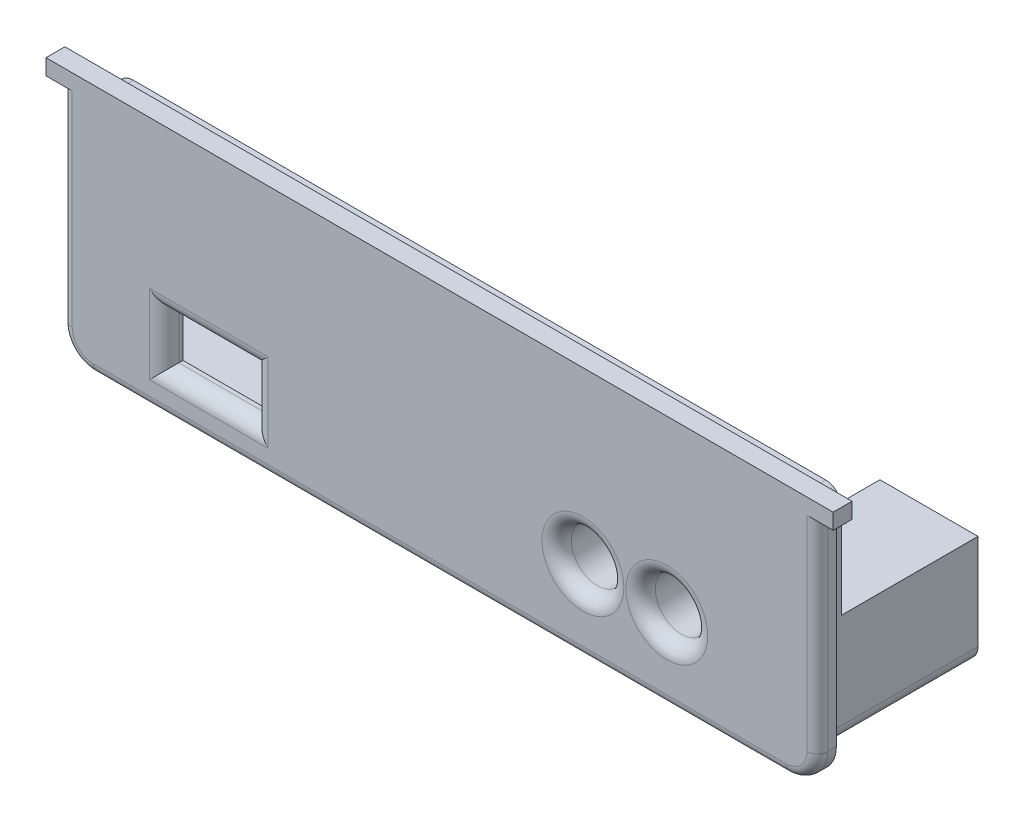
SolidWorks part; units mm, degrees
ref_plane "Front Plane" through (0, 0, 0) normal (0, 0, 1) x (1, 0, 0)
ref_plane "Top Plane" through (0, 0, 0) normal (0, 1, 0) x (1, 0, 0)
ref_plane "Right Plane" through (0, 0, 0) normal (1, 0, 0) x (0, 0, -1)
sketch "Sketch1" plane through (0, 0, 0) normal (0, 0, 1) x (1, 0, 0)
  line L1 (0, 0) -> (72, 0)
  line L2 (0, 0) -> (0, 22.5)
  line L3 (0, 24) -> (72, 24)
  line L4 (72, 0) -> (72, 22.5)
  line L5 (0, 24) -> (-1.5, 24)
  line L7 (0, 22.5) -> (-1.5, 22.5)
  line L8 (-1.5, 24) -> (-1.5, 22.5)
  line L9 (72, 24) -> (73.5, 24)
  line L11 (72, 22.5) -> (73.5, 22.5)
  line L12 (73.5, 24) -> (73.5, 22.5)
  dimension "D1" = 24
  dimension "D2" = 72
  dimension "D3" = 1.5
  dimension "D4" = 1.5
  dimension "D5" = 1.5
  dimension "D6" = 1.5
  dimension "D7" = 72
extrude "Boss-Extrude1" add sketch "Sketch1" along normal blind 1.8
sketch "Sketch2" plane through (0, 0, 0) normal (0, 0, -1) x (-1, 0, 0)
  line L0 (-73.5, 24) -> (1.5, 24) construction
  line L1 (-70.5, 22.5) -> (-1.5, 22.5)
  line L2 (-70.5, 22.5) -> (-70.5, 1.5)
  line L3 (-70.5, 1.5) -> (-1.5, 1.5)
  line L4 (-1.5, 22.5) -> (-1.5, 1.5)
  line L5 (-72, 0) -> (-72, 22.5) construction
  line L6 (0, 0) -> (-72, 0) construction
  line L7 (0, 22.5) -> (0, 0) construction
  line L9 (-68.5, 20.5) -> (-3.5, 20.5)
  line L10 (-68.5, 20.5) -> (-68.5, 3.5)
  line L11 (-68.5, 3.5) -> (-3.5, 3.5)
  line L12 (-3.5, 20.5) -> (-3.5, 3.5)
  dimension "D1" = 1.5
  dimension "D2" = 1.5
  dimension "D3" = 1.5
  dimension "D4" = 1.5
  dimension "D5" = 2
  dimension "D6" = 2
  dimension "D7" = 2
  dimension "D8" = 2
extrude "Boss-Extrude2" add sketch "Sketch2" along normal blind 15
sketch "Sketch3" plane through (0, 0, -15) normal (0, 0, -1) x (-1, 0, 0)
  line L0 (-3.5, 3.5) -> (-3.5, 20.5) construction
  line L1 (-3.5, 6) -> (-1.5, 6)
  line L2 (-3.5, 6) -> (-3.5, 20.5)
  line L3 (-3.5, 20.5) -> (-1.5, 20.5)
  line L4 (-1.5, 6) -> (-1.5, 20.5)
  line L5 (-1.5, 1.5) -> (-1.5, 22.5) construction
  line L6 (-70.5, 1.5) -> (-1.5, 1.5) construction
  dimension "D1" = 4.5
extrude "Cut-Extrude2" cut sketch "Sketch3" against normal blind 15
sketch "Sketch4" plane through (0, 0, -15) normal (0, 0, -1) x (-1, 0, 0)
  line L1 (-70.5, 22.5) -> (-1.5, 22.5)
  line L2 (-70.5, 22.5) -> (-70.5, 12.1)
  line L3 (-70.5, 12.1) -> (-1.5, 12.1)
  line L4 (-1.5, 22.5) -> (-1.5, 12.1)
  dimension "D1" = 10.4
extrude "Cut-Extrude4" cut sketch "Sketch4" against normal blind 13
sketch "Sketch7" plane through (0, 0, -15) normal (0, 0, -1) x (-1, 0, 0)
  line L0 (-68.5, 3.5) -> (-3.5, 3.5) construction
  line L1 (-68.5, 12.1) -> (-61.1519, 12.1)
  line L2 (-68.5, 12.1) -> (-68.5, 10.5)
  line L3 (-68.5, 10.5) -> (-62.7519, 10.5)
  line L4 (-61.1519, 12.1) -> (-61.1519, 10.5)
  line L6 (-61.1519, 10.5) -> (-61.1519, 3.5)
  line L7 (-61.1519, 3.5) -> (-62.7519, 3.5)
  line L8 (-62.7519, 10.5) -> (-62.7519, 3.5)
  dimension "D1" = 1.6
  dimension "D2" = 1.6
extrude "Boss-Extrude4" add sketch "Sketch7" against normal blind 15
sketch "Sketch8" plane through (0, 0, 0) normal (0, 0, -1) x (-1, 0, 0)
  line L1 (-61.1519, 3.5) -> (-45.1519, 3.5)
  line L2 (-61.1519, 3.5) -> (-61.1519, 12.1)
  line L3 (-61.1519, 12.1) -> (-45.1519, 12.1)
  line L4 (-45.1519, 3.5) -> (-45.1519, 12.1)
  dimension "D1" = 16
extrude "Boss-Extrude5" add sketch "Sketch8" along normal blind 10
sketch "Sketch9" plane through (0, 0, -10) normal (0, 0, -1) x (-1, 0, 0)
  line L0 (-45.1519, 7.8) -> (-61.1519, 7.8) construction
  line L1 (-45.1519, 3.5) -> (-45.1519, 12.1) construction
  line L2 (-61.1519, 12.1) -> (-61.1519, 3.5) construction
  circle A0 centre (-49.6519, 7.8) radius 2.5
  circle A1 centre (-57.6519, 7.8) radius 2.5
  dimension "D1" = 5
  dimension "D2" = 5
  dimension "D3" = 8
  dimension "D4" = 4.5
extrude "Cut-Extrude5" cut sketch "Sketch9" against normal blind 12
sketch "Sketch10" plane through (0, 0, -10) normal (0, 0, -1) x (-1, 0, 0)
  line L0 (-57.6519, 7.8) -> (-49.6519, 7.8) construction
  line L1 (-57.6519, 11.3) -> (-49.6519, 11.3)
  line L2 (-57.6519, 4.3) -> (-49.6519, 4.3)
  arc A0 (-57.6519, 11.3) -> (-57.6519, 4.3) centre (-57.6519, 7.8) ccw
  arc A1 (-49.6519, 4.3) -> (-49.6519, 11.3) centre (-49.6519, 7.8) ccw
  point P4 (-53.6519, 7.8)
  dimension "D1" = 7
extrude "Cut-Extrude6" cut sketch "Sketch10" against normal blind 4
fillet "Fillet1" radius 1.4 2 edges at (60.1519, 7.8, 1.8) (52.1519, 7.8, 1.8)
sketch "Sketch11" plane through (0, 0, 1.8) normal (0, 0, 1) x (1, 0, 0)
  line L0 (0, 22.5) -> (0, 0) construction
  line L1 (9.75, 8.5) -> (18.25, 8.5)
  line L2 (9.75, 8.5) -> (9.75, 3.75)
  line L3 (9.75, 3.75) -> (18.25, 3.75)
  line L4 (18.25, 8.5) -> (18.25, 3.75)
  line L5 (73.5, 24) -> (-1.5, 24) construction
  dimension "D1" = 8.5
  dimension "D2" = 4.75
  dimension "D3" = 18.25
  dimension "D4" = 20.25
extrude "Cut-Extrude7" cut sketch "Sketch11" against normal blind 4
fillet "Fillet2" radius 1.4 4 edges at (18.25, 6.125, 1.8) (14, 8.5, 1.8) (9.75, 6.125, 1.8) (14, 3.75, 1.8)
fillet "Fillet6" radius 1.5 2 edges at (1.5, 1.5, -7.5) (70.5, 1.5, -7.5)
fillet "Fillet7" radius 1.5 2 edges at (1.5, 22.5, -1) (70.5, 22.5, -1)
fillet "Fillet8" radius 3 2 edges at (72, 0, 0.9) (0, 0, 0.9)
fillet "Fillet9" radius 1 5 edges at (72, 12.75, 1.8) (71.1213, 0.8787, 1.8) (36, 0, 1.8) (0.8787, 0.8787, 1.8) (0, 12.75, 1.8)
